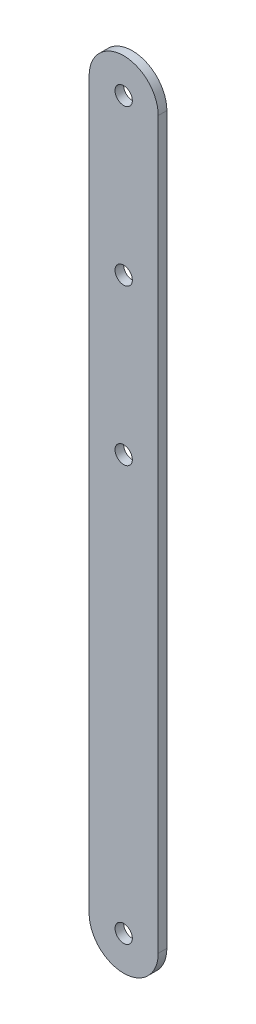
SolidWorks part; units mm, degrees
material "5052-H32"
ref_plane "Front Plane" through (0, 0, 0) normal (0, 0, 1) x (1, 0, 0)
ref_plane "Top Plane" through (0, 0, 0) normal (0, 1, 0) x (1, 0, 0)
ref_plane "Right Plane" through (0, 0, 0) normal (1, 0, 0) x (0, 0, -1)
sketch "Sketch1" plane through (0, 0, 0) normal (0, 0, 1) x (1, 0, 0)
  line L0 (-50.8, -1066.8) -> (-50.8, 0)
  line L1 (50.8, 0) -> (50.8, -1066.8)
  line L2 (0, -457.2) -> (0, -228.6) construction
  line L3 (0, 0) -> (0, -228.6) construction
  arc A0 (50.8, 0) -> (-50.8, 0) centre (0, 0) ccw
  arc A1 (-50.8, -1066.8) -> (50.8, -1066.8) centre (0, -1066.8) ccw
  circle A2 centre (0, 0) radius 12.7
  circle A3 centre (0, -1066.8) radius 12.7
  circle A5 centre (0, -228.6) radius 12.7
  circle A6 centre (0, -457.2) radius 12.7
  dimension "D1" = 50.8
  dimension "D3" = 25.4
  dimension "D4" = 25.4
  dimension "D5" = 228.6
  dimension "D2" = 1066.8
  dimension "D6" = 228.6
extrude "Boss-Extrude1" add sketch "Sketch1" along normal blind 12.7
sketch "Sketch2" plane through (0, 0, 12.7) normal (0, 0, 1) x (1, 0, 0)
  line L0 (0, -1066.8) -> (-381, -1726.7114) construction
  line L1 (0, -1066.8) -> (0, -939.8) construction
  line L2 (0, -939.8) -> (-437.0652, -1563.9939) construction
  line L3 (0, -812.8) -> (-489.8042, -1396.5259) construction
  line L4 (0, -685.8) -> (-538.8154, -1224.6154) construction
  line L5 (0, -558.8) -> (-583.7259, -1048.6042) construction
  line L6 (0, -431.8) -> (-624.1939, -868.8652) construction
  line L7 (0, -939.8) -> (0, -812.8) construction
  line L8 (0, -812.8) -> (0, -685.8) construction
  line L9 (0, -685.8) -> (0, -558.8) construction
  line L10 (0, -558.8) -> (0, -431.8) construction
  dimension "D1" = 762
  dimension "D2" = 150
  dimension "D3" = 5
  dimension "D4" = 127
  dimension "D5" = 5
  dimension "D6" = 5
  dimension "D7" = 5
  dimension "D8" = 5
